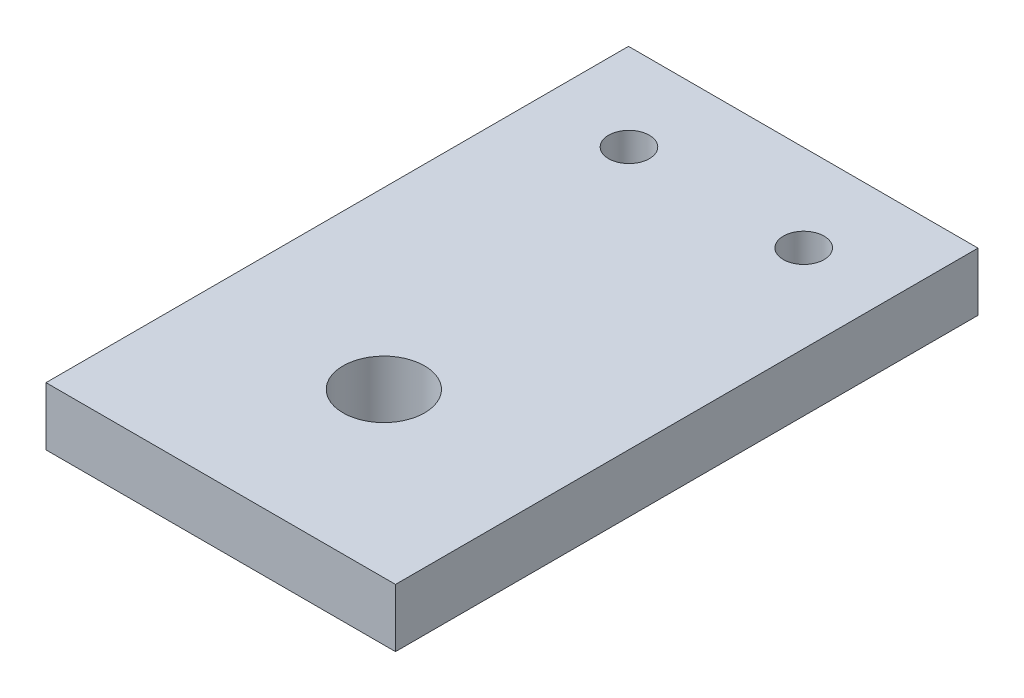
SolidWorks part; units mm, degrees
ref_plane "정면" through (0, 0, 0) normal (0, 0, 1) x (1, 0, 0)
ref_plane "윗면" through (0, 0, 0) normal (0, 1, 0) x (1, 0, 0)
ref_plane "우측면" through (0, 0, 0) normal (1, 0, 0) x (0, 0, -1)
sketch "스케치2" plane through (0, 0, 0) normal (0, 1, 0) x (1, 0, 0)
  line L0 (15, 36) -> (-15, 36)
  line L1 (15, 36) -> (15, -14)
  line L2 (-15, 36) -> (-15, -14)
  line L3 (15, -14) -> (-15, -14)
  line L4 (15, 36) -> (-15, -14) construction
  line L5 (-15, 36) -> (15, -14) construction
  line L6 (0, 0) -> (0, -14) construction
  circle A0 centre (0, 0) radius 3.5
  point P4 (0, 11)
  dimension "D1" = 7
  dimension "D2" = 14
  dimension "D3" = 50
  dimension "D4" = 30
extrude "보스-돌출1" add sketch "스케치2" along normal blind 5
sketch "스케치4" plane through (0, 0, 0) normal (0, -1, 0) x (1, 0, 0)
  line L0 (15, -28.5391) -> (7.5, -28.5391) construction
  line L1 (15, 14) -> (15, -36) construction
  line L2 (7.5, -28.5391) -> (-7.5, -28.5391) construction
  line L3 (-7.5, -28.5391) -> (-15, -28.5391) construction
  line L4 (-15, -36) -> (-15, 14) construction
  circle A0 centre (7.5, -28.5391) radius 1.75
  circle A1 centre (-7.5, -28.5391) radius 1.75
  dimension "D1" = 3.5
  dimension "D2" = 15
extrude "컷-돌출1" cut sketch "스케치4" against normal blind 10
